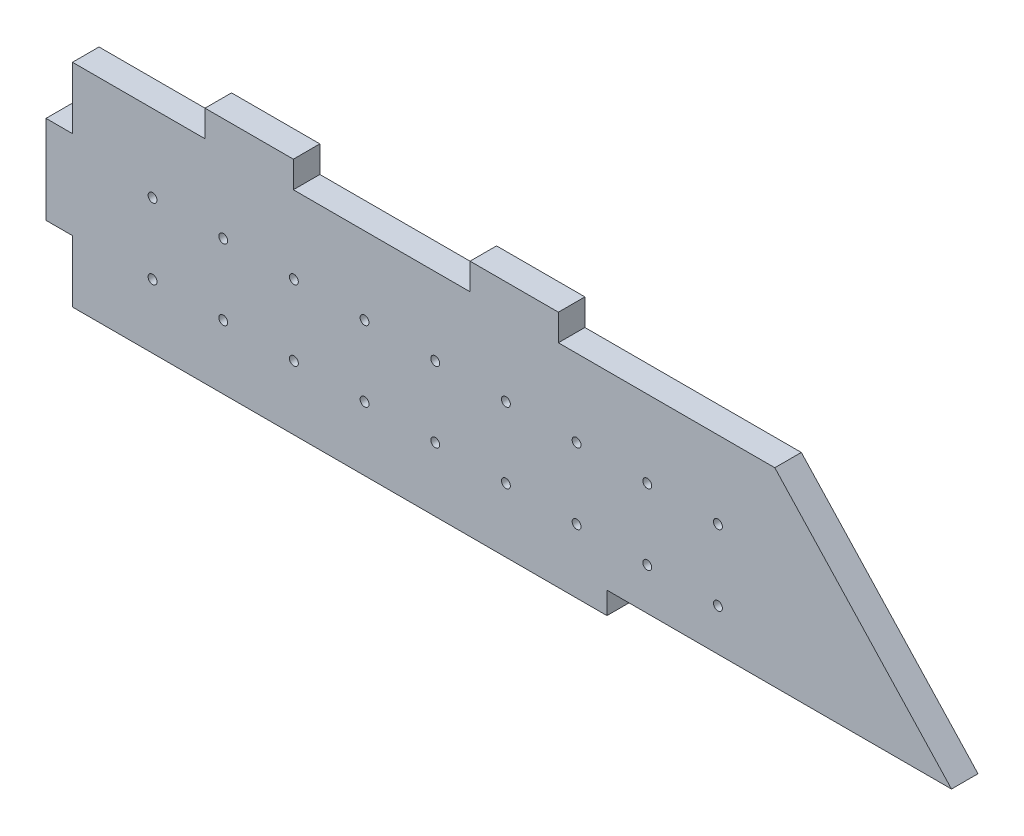
SolidWorks part; units mm, degrees
ref_plane "Plan de face" through (0, 0, 0) normal (0, 0, 1) x (1, 0, 0)
ref_plane "Plan de dessus" through (0, 0, 0) normal (0, 1, 0) x (1, 0, 0)
ref_plane "Plan de droite" through (0, 0, 0) normal (1, 0, 0) x (0, 0, -1)
sketch "Esquisse1" plane through (0, 0, 0) normal (0, 0, 1) x (1, 0, 0)
  line L1 (0, 0) -> (-199, 0)
  line L2 (0, 0) -> (0, 48)
  line L3 (0, 48) -> (-199, 48)
  line L4 (-199, 0) -> (-199, 48)
  dimension "D1" = 48
  dimension "D2" = 199
extrude "Boss.-Extru.1" add sketch "Esquisse1" along normal blind 6
sketch "Esquisse2" plane through (0, 48, 0) normal (0, 1, 0) x (1, 0, 0)
  line L0 (0, -6) -> (-199, -6) construction
  line L1 (-89, -6) -> (-109, -6)
  line L2 (-89, -6) -> (-89, 0)
  line L3 (-89, 0) -> (-109, 0)
  line L4 (-109, -6) -> (-109, 0)
  line L5 (0, 0) -> (-199, 0) construction
  line L6 (-199, -6) -> (-199, 0) construction
  line L7 (-149, -6) -> (-169, -6)
  line L8 (-149, -6) -> (-149, 0)
  line L9 (-149, 0) -> (-169, 0)
  line L10 (-169, -6) -> (-169, 0)
  dimension "D1" = 20
  dimension "D2" = 20
  dimension "D3" = 40
  dimension "D4" = 30
extrude "Boss.-Extru.2" add sketch "Esquisse2" along normal blind 6
sketch "Esquisse3" plane through (-199, 0, 0) normal (-1, 0, 0) x (0, 0, 1)
  line L1 (6, 48) -> (6, 0) construction
  line L2 (6, 34) -> (0, 34)
  line L3 (6, 34) -> (6, 14)
  line L4 (6, 14) -> (0, 14)
  line L6 (0, 34) -> (0, 14)
  line L7 (0, 48) -> (0, 0) construction
  line L8 (6, 48) -> (0, 48) construction
  dimension "D1" = 20
  dimension "D2" = 14
extrude "Boss.-Extru.3" add sketch "Esquisse3" along normal blind 6
sketch "Esquisse4" plane through (0, 0, 6) normal (0, 0, 1) x (1, 0, 0)
  line L1 (0, 0) -> (-78, 0)
  line L2 (0, 0) -> (0, 5)
  line L3 (0, 5) -> (-78, 5)
  line L4 (-78, 0) -> (-78, 5)
  dimension "D1" = 5
  dimension "D2" = 78
extrude "Enlèv. mat.-Extru.1" cut sketch "Esquisse4" against normal through all
sketch "Esquisse5" plane through (0, 0, 6) normal (0, 0, 1) x (1, 0, 0)
  line L0 (0, 48) -> (-40, 48)
  line L1 (0, 48) -> (-89, 48) construction
  line L2 (-40, 48) -> (0, 5)
  line L3 (0, 5) -> (0, 48)
  dimension "D1" = 159
extrude "Enlèv. mat.-Extru.2" cut sketch "Esquisse5" against normal through all
sketch "Esquisse6" plane through (0, 0, 6) normal (0, 0, 1) x (1, 0, 0)
  line L0 (-199, 0) -> (-78, 0) construction
  line L1 (-199, 14) -> (-199, 0) construction
  line L2 (-199, 48) -> (-199, 34) construction
  line L3 (-148.88, 14.5) -> (-164.88, 14.5) construction
  line L5 (-199, 0) -> (-78, 0) construction
  circle A0 centre (-148.88, 14.5) radius 1.005
  circle A1 centre (-148.88, 30.5) radius 1.005
  circle A2 centre (-132.88, 14.5) radius 1.005
  circle A3 centre (-132.88, 30.5) radius 1.005
  circle A4 centre (-116.88, 14.5) radius 1.005
  circle A5 centre (-116.88, 30.5) radius 1.005
  circle A6 centre (-100.88, 14.5) radius 1.005
  circle A7 centre (-100.88, 30.5) radius 1.005
  circle A8 centre (-84.88, 14.5) radius 1.005
  circle A9 centre (-84.88, 30.5) radius 1.005
  circle A10 centre (-68.88, 14.5) radius 1.005
  circle A11 centre (-68.88, 30.5) radius 1.005
  circle A12 centre (-52.88, 14.5) radius 1.005
  circle A13 centre (-52.88, 30.5) radius 1.005
  circle A14 centre (-164.88, 14.5) radius 1.005
  circle A15 centre (-164.88, 30.5) radius 1.005
  circle A16 centre (-180.88, 14.5) radius 1.005
  circle A17 centre (-180.88, 30.5) radius 1.005
  dimension "D1" = 2.01
  dimension "D2" = 2.01
  dimension "D3" = 2.01
  dimension "D4" = 2.01
  dimension "D12" = 50.12
  dimension "D16" = 14.5
  dimension "D17" = 14.5
  dimension "D18" = 16
  dimension "D5" = 16
  dimension "D6" = 16
  dimension "D7" = 16
  dimension "D8" = 16
  dimension "D9" = 14.5
  dimension "D10" = 50.12
  dimension "D11" = 14.5
  dimension "D15" = 16
  dimension "D13" = 6
  dimension "D14" = 3
extrude "Enlèv. mat.-Extru.3" cut sketch "Esquisse6" against normal through all
sketch "Esquisse7" plane through (0, 0, 0) normal (0, 0, -1) x (-1, 0, 0)
  line L0 (199, 0) -> (78, 0) construction
  circle A0 centre (180.88, 14.5) radius 2
  circle A1 centre (180.88, 30.5) radius 2
  circle A2 centre (164.88, 14.5) radius 2
  circle A3 centre (164.88, 30.5) radius 2
  circle A4 centre (148.88, 14.5) radius 2
  circle A5 centre (148.88, 30.5) radius 2
  circle A6 centre (132.88, 14.5) radius 2
  circle A7 centre (132.88, 30.5) radius 2
  circle A8 centre (116.88, 14.5) radius 2
  circle A9 centre (116.88, 30.5) radius 2
  circle A10 centre (100.88, 14.5) radius 2
  circle A11 centre (100.88, 30.5) radius 2
  circle A12 centre (84.88, 14.5) radius 2
  circle A13 centre (84.88, 30.5) radius 2
  circle A14 centre (68.88, 14.5) radius 2
  circle A15 centre (68.88, 30.5) radius 2
  circle A16 centre (52.88, 14.5) radius 2
  circle A17 centre (52.88, 30.5) radius 2
  dimension "D1" = 4
  dimension "D2" = 4
  dimension "D4" = 14.5
  dimension "D5" = 16
  dimension "D3" = 9
extrude "Enlèv. mat.-Extru.4" cut sketch "Esquisse7" against normal blind 3
